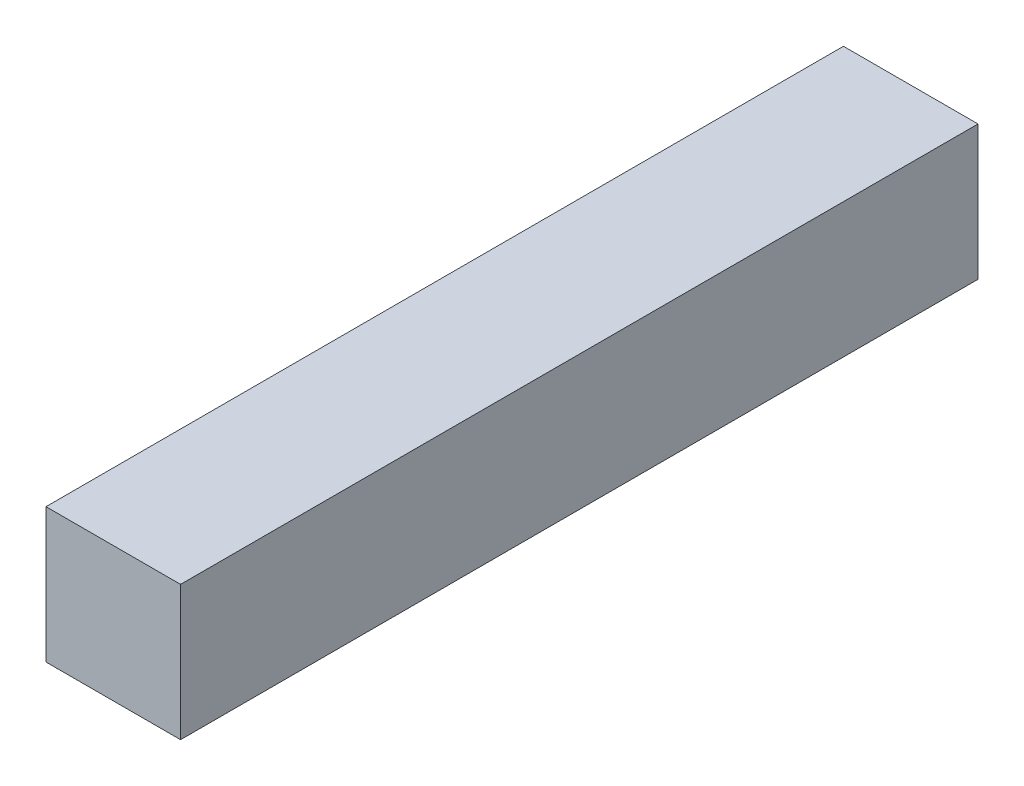
SolidWorks part; units mm, degrees
ref_plane "Front Plane" through (0, 0, 0) normal (0, 0, 1) x (1, 0, 0)
ref_plane "Top Plane" through (0, 0, 0) normal (0, 1, 0) x (1, 0, 0)
ref_plane "Right Plane" through (0, 0, 0) normal (1, 0, 0) x (0, 0, -1)
sketch "Sketch1" plane through (0, 0, 0) normal (0, 0, 1) x (1, 0, 0)
  line L1 (-15, -15) -> (15, -15)
  line L2 (-15, -15) -> (-15, 15)
  line L3 (-15, 15) -> (15, 15)
  line L4 (15, -15) -> (15, 15)
  line L5 (-15, -15) -> (15, 15) construction
  line L6 (-15, 15) -> (15, -15) construction
  point P0 (0, 0)
  dimension "D1" = 30
extrude "Boss-Extrude1" add sketch "Sketch1" along normal blind 177.8
